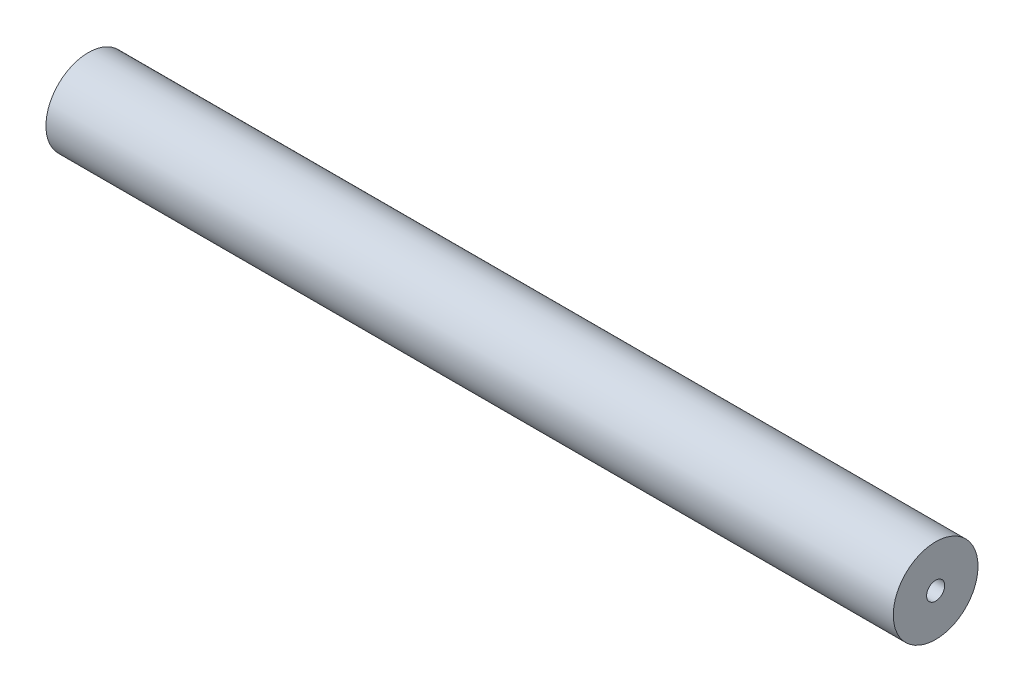
SolidWorks part; units mm, degrees
ref_plane "前视基准面" through (0, 0, 0) normal (0, 0, 1) x (1, 0, 0)
ref_plane "上视基准面" through (0, 0, 0) normal (0, 1, 0) x (1, 0, 0)
ref_plane "右视基准面" through (0, 0, 0) normal (1, 0, 0) x (0, 0, -1)
sketch "草图1" plane through (0, 0, 0) normal (1, 0, 0) x (0, 0, -1)
  circle A0 centre (0, 0) radius 7.5
  circle A1 centre (0, 0) radius 1.6
  dimension "D1" = 15
  dimension "D2" = 3.2
extrude "凸台-拉伸1" add sketch "草图1" along normal blind 150
